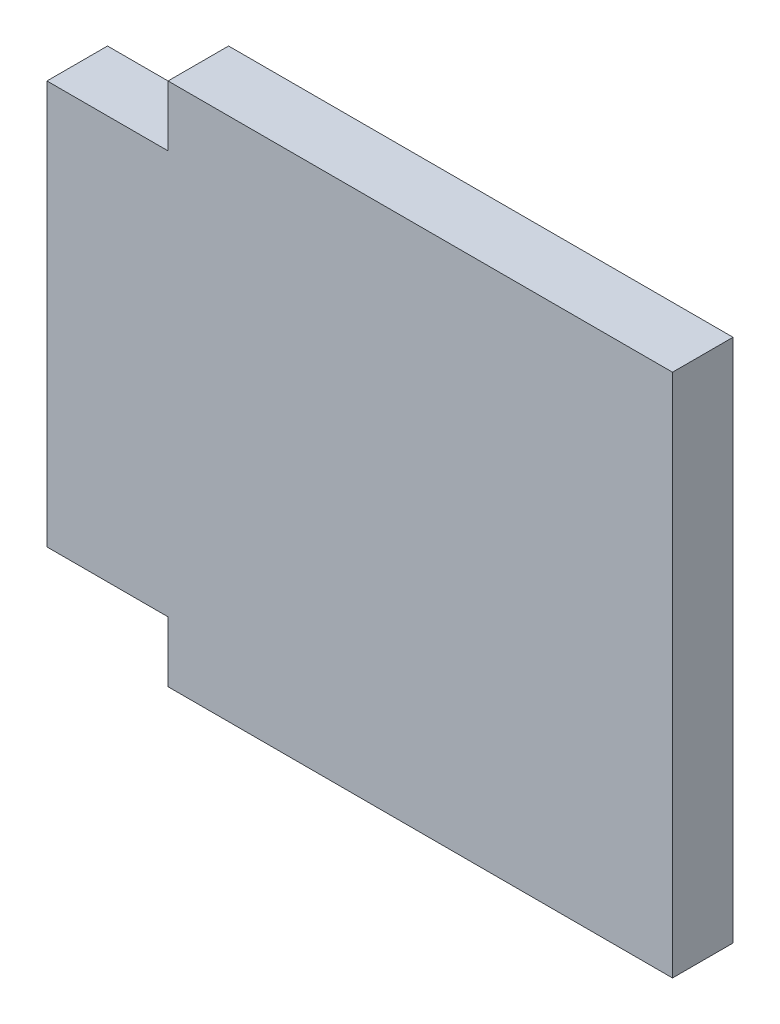
SolidWorks part; units mm, degrees
ref_plane "Ön Düzlem" through (0, 0, 0) normal (0, 0, 1) x (1, 0, 0)
ref_plane "Üst Düzlem" through (0, 0, 0) normal (0, 1, 0) x (1, 0, 0)
ref_plane "Sağ Düzlem" through (0, 0, 0) normal (1, 0, 0) x (0, 0, -1)
sketch "Çizim1" plane through (0, 0, 0) normal (0, 0, 1) x (1, 0, 0)
  line L0 (0, 0) -> (0, 20)
  line L1 (0, 20) -> (6, 20)
  line L2 (6, 20) -> (6, 23)
  line L3 (6, 23) -> (31, 23)
  line L4 (31, 23) -> (31, -3)
  line L5 (31, -3) -> (6, -3)
  line L6 (6, -3) -> (6, 0)
  line L7 (6, 0) -> (0, 0)
extrude "Yükseklik-Ekstrüzyon1" add sketch "Çizim1" along normal blind 3
